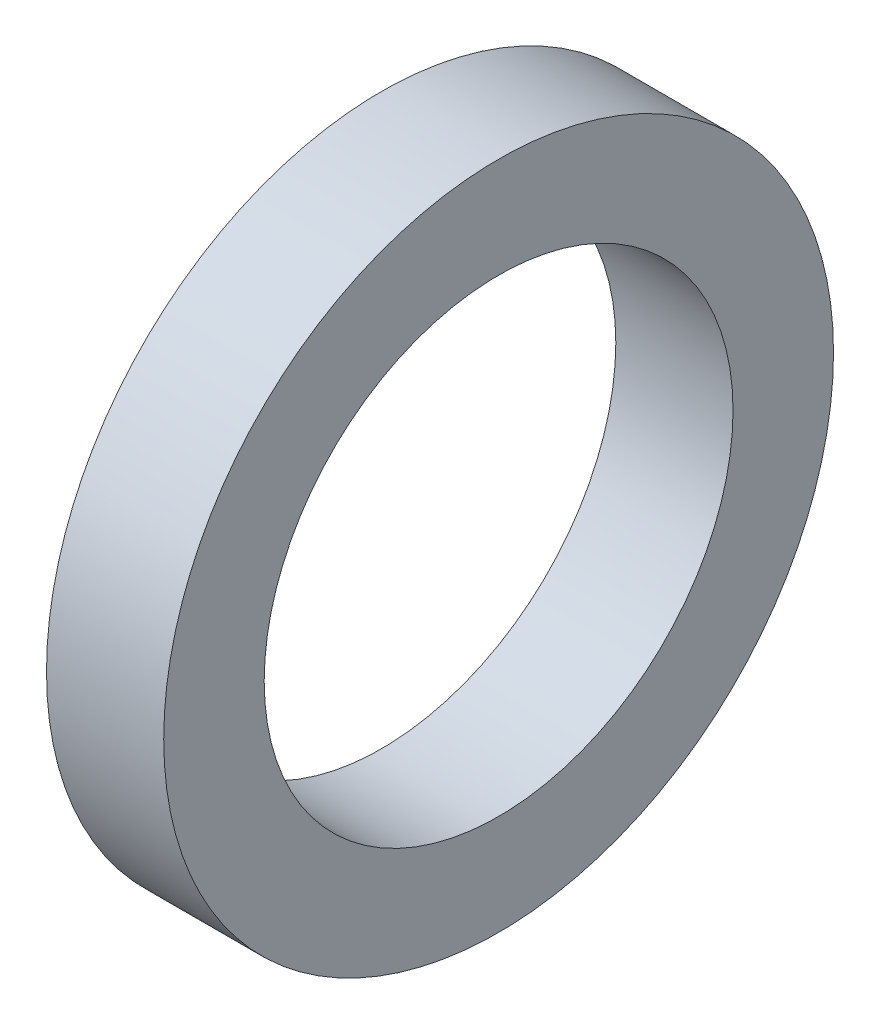
SolidWorks part; units mm, degrees
ref_plane "Front Plane" through (0, 0, 0) normal (0, 0, 1) x (1, 0, 0)
ref_plane "Top Plane" through (0, 0, 0) normal (0, 1, 0) x (1, 0, 0)
ref_plane "Right Plane" through (0, 0, 0) normal (1, 0, 0) x (0, 0, -1)
sketch "Sketch1" plane through (0, 0, 0) normal (0, 0, 1) x (1, 0, 0)
  line L0 (0, 0) -> (3.5, 0) construction
  line L1 (0, 10) -> (0, 7)
  line L2 (0, 7) -> (3.5, 7)
  line L3 (3.5, 7) -> (3.5, 10)
  line L4 (3.5, 10) -> (0, 10)
  dimension "D1" = 3.5
  dimension "D2" = 14
  dimension "D3" = 20
revolve "Revolve1" add sketch "Sketch1" angle 360 about L0
